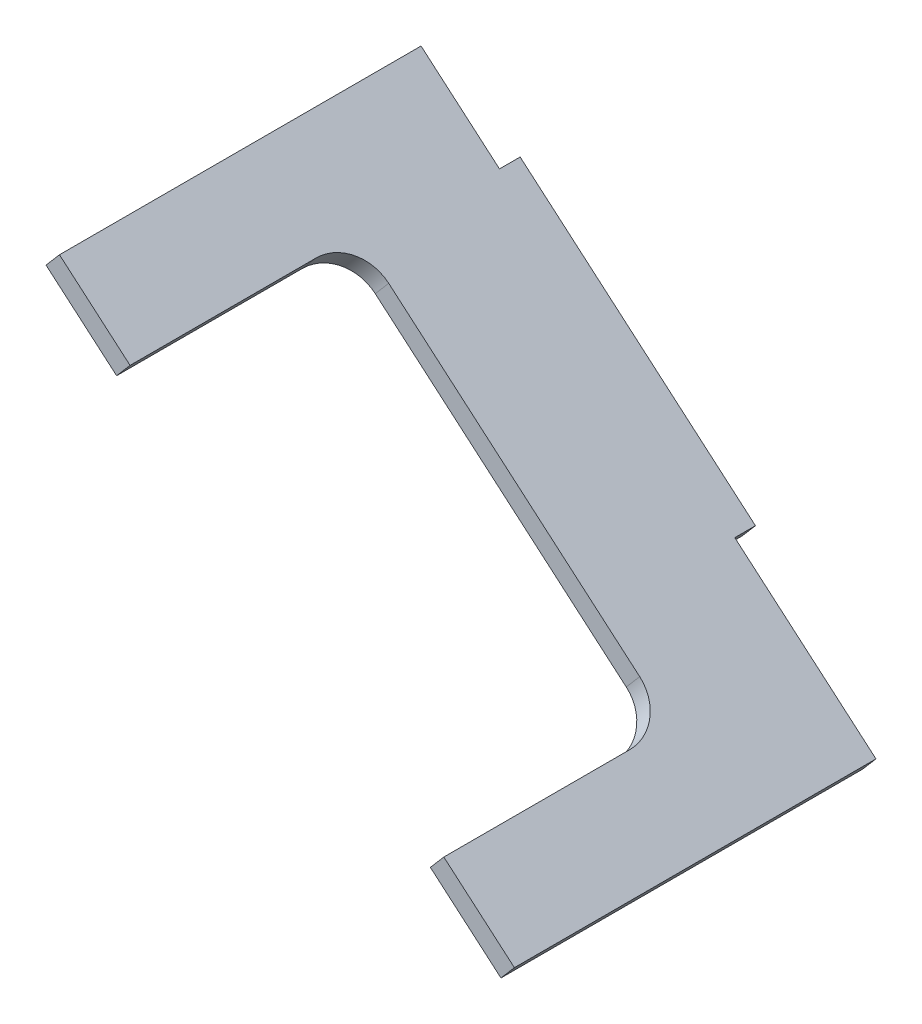
SolidWorks part; units mm, degrees
material "PVC rigido"
ref_plane "Piano frontale" through (0, 0, 0) normal (0, 0, 1) x (1, 0, 0)
ref_plane "Piano superiore" through (0, 0, 0) normal (0, 1, 0) x (1, 0, 0)
ref_plane "Piano destro" through (0, 0, 0) normal (1, 0, 0) x (0, 0, -1)
sketch "Schizzo1" plane through (0, 0, 0) normal (0, 0, 1) x (1, 0, 0)
  line L0 (54.746, 47.0338) -> (31.9679, 66.557) construction
  line L1 (53.4445, 45.5153) -> (54.746, 47.0338) construction
  line L2 (30.6663, 65.0385) -> (53.4445, 45.5153) construction
  line L3 (31.9679, 66.557) -> (30.6663, 65.0385) construction
  line L4 (54.746, 47.0338) -> (31.9679, 66.557)
  line L5 (53.4445, 45.5153) -> (54.746, 47.0338)
  line L6 (30.6663, 65.0385) -> (53.4445, 45.5153)
  line L7 (31.9679, 66.557) -> (30.6663, 65.0385)
extrude "Estrusione-Estrusione1" add sketch "Schizzo1" along normal up to surface (35 mm away) and the other way up to surface (2 mm away)
sketch "Schizzo2" plane through (45.1238, 52.647, 0) normal (-0.6508, -0.7593, 0) x (0.7593, -0.6508, 0)
  line L0 (-19.0412, 0) -> (10.9588, 0) construction
  line L1 (-19.0412, 0) -> (-29.0412, 0)
  line L2 (-19.0412, 0) -> (-19.0412, 35)
  line L3 (-19.0412, 35) -> (-29.0412, 35)
  line L4 (-29.0412, 0) -> (-29.0412, 35)
  line L5 (-19.0412, 35) -> (-19.0412, -2) construction
  line L6 (10.9588, 35) -> (-19.0412, 35) construction
  line L7 (10.9588, 0) -> (28.9588, 0)
  line L8 (10.9588, 0) -> (10.9588, 35)
  line L9 (10.9588, 35) -> (28.9588, 35)
  line L10 (28.9588, 0) -> (28.9588, 35)
  line L11 (10.9588, 35) -> (10.9588, -2) construction
  dimension "D1" = 10
  dimension "D2" = 18
extrude "Estrusione-Estrusione2" add sketch "Schizzo2" against normal up to surface (2 mm away) up to face at (43.357, 56.7954, 16.5)
sketch "Schizzo3" plane through (46.4253, 54.1655, 0) normal (0.6508, 0.7593, 0) x (0.7593, -0.6508, 0)
  line L0 (-29.0412, -35) -> (28.9588, -35) construction
  line L1 (-20.0412, -35) -> (19.9588, -35)
  line L2 (-20.0412, -35) -> (-20.0412, -13)
  line L3 (-20.0412, -13) -> (19.9588, -13)
  line L4 (19.9588, -35) -> (19.9588, -13)
  line L5 (-20.0412, -13) -> (-29.0412, -13) construction
  line L7 (-29.0412, 0) -> (-29.0412, -35) construction
  dimension "D1" = 22
  dimension "D2" = 40
  dimension "D3" = 9
extrude "Taglio-Estrusione1" cut sketch "Schizzo3" against normal blind 10
fillet "Raccordo1" radius 4 2 edges at (60.9287, 40.4176, 13) (30.5578, 66.4485, 13)
